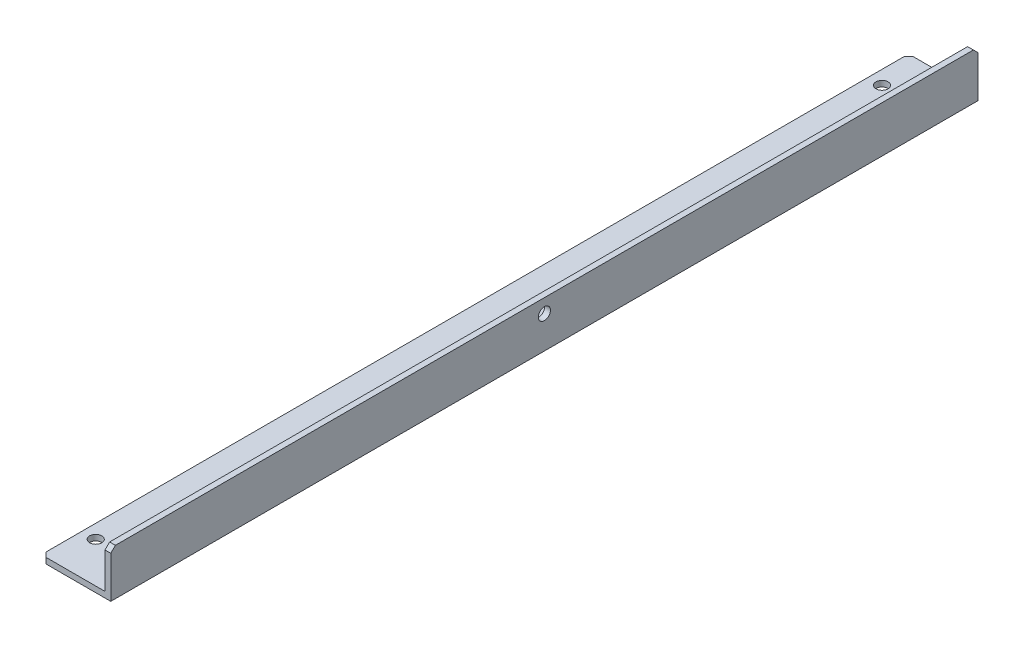
SolidWorks part; units mm, degrees
material "5454-H111"
ref_plane "Front Plane" through (0, 0, 0) normal (0, 0, 1) x (1, 0, 0)
ref_plane "Top Plane" through (0, 0, 0) normal (0, 1, 0) x (1, 0, 0)
ref_plane "Right Plane" through (0, 0, 0) normal (1, 0, 0) x (0, 0, -1)
sketch "Sketch1" plane through (0, 0, 0) normal (0, 0, 1) x (1, 0, 0)
  line L0 (0, 0) -> (-60, 0)
  line L1 (-60, 0) -> (-60, 5)
  line L2 (-60, 5) -> (-5, 5)
  line L3 (-5, 5) -> (-5, 40)
  line L4 (-5, 40) -> (0, 40)
  line L5 (0, 40) -> (0, 0)
  dimension "D1" = 5
  dimension "D2" = 40
  dimension "D3" = 60
extrude "Boss-Extrude1" add sketch "Sketch1" along normal blind 750
ref_plane "Plane1" through (-60, 5, 0) normal (0, 0, -1) x (-1, 0, 0)
sketch "Sketch4" plane through (0, 5, 0) normal (0, 1, 0) x (1, 0, 0)
  line L0 (146.25, 0) -> (-266.25, 0) construction
  line L1 (-60, -750) -> (-60, 0) construction
  line L2 (-1060, -375) -> (48940, -375) construction
  circle A0 centre (-48, -35) radius 5.25
  circle A1 centre (-48, -715) radius 5.25
  point P10 (-60, -375)
  dimension "D1" = 10.5
  dimension "D2" = 35
  dimension "D3" = 12
extrude "Cut-Extrude1" cut sketch "Sketch4" against normal up to next
sketch "Sketch5" plane through (-5, 0, 0) normal (-1, 0, 0) x (0, 0, 1)
  line L0 (375, -960) -> (375, 49040) construction
  line L1 (750, 40) -> (0, 40) construction
  circle A0 centre (375, 28) radius 5.25
  point P5 (375, 40)
  dimension "D1" = 10.5
  dimension "D2" = 12
extrude "Cut-Extrude2" cut sketch "Sketch5" against normal up to next
chamfer "Chamfer1" distance 4 angle 45 4 edges at (-60, 2.5, 0) (-2.5, 40, 0) (-2.5, 40, 750) (-60, 2.5, 750)
